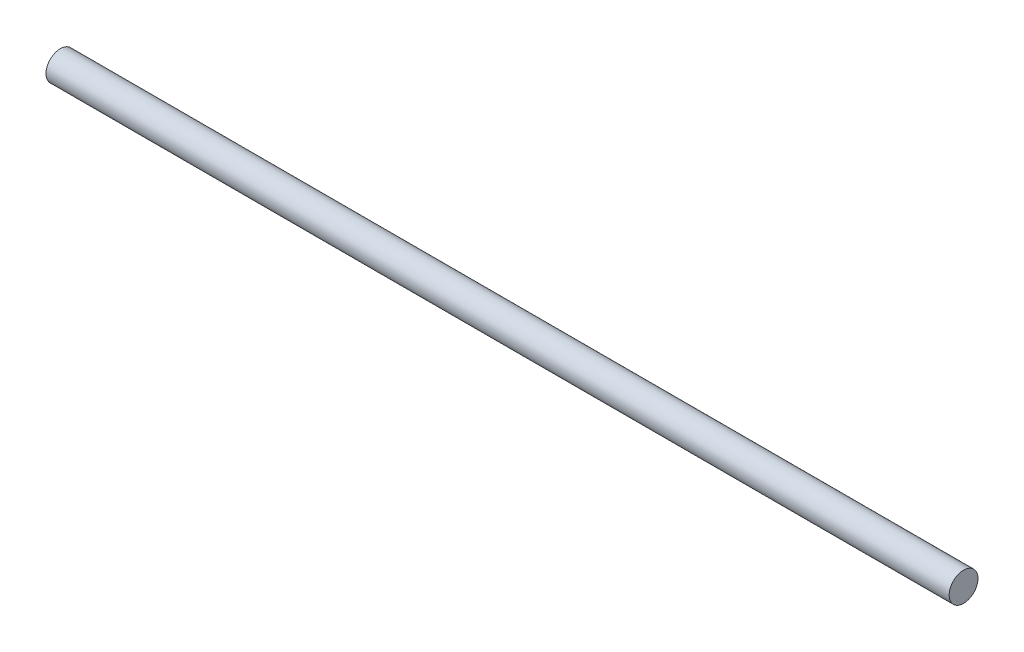
SolidWorks part; units mm, degrees
material "AISI Type A2 Tool Steel"
ref_plane "Front Plane" through (0, 0, 0) normal (0, 0, 1) x (1, 0, 0)
ref_plane "Top Plane" through (0, 0, 0) normal (0, 1, 0) x (1, 0, 0)
ref_plane "Right Plane" through (0, 0, 0) normal (1, 0, 0) x (0, 0, -1)
sketch "Sketch1" plane through (0, 0, 0) normal (1, 0, 0) x (0, 0, -1)
  circle A0 centre (0, 0) radius 4.7625
  dimension "D1" = 9.525
extrude "Boss-Extrude1" add sketch "Sketch1" along normal blind 298.45
